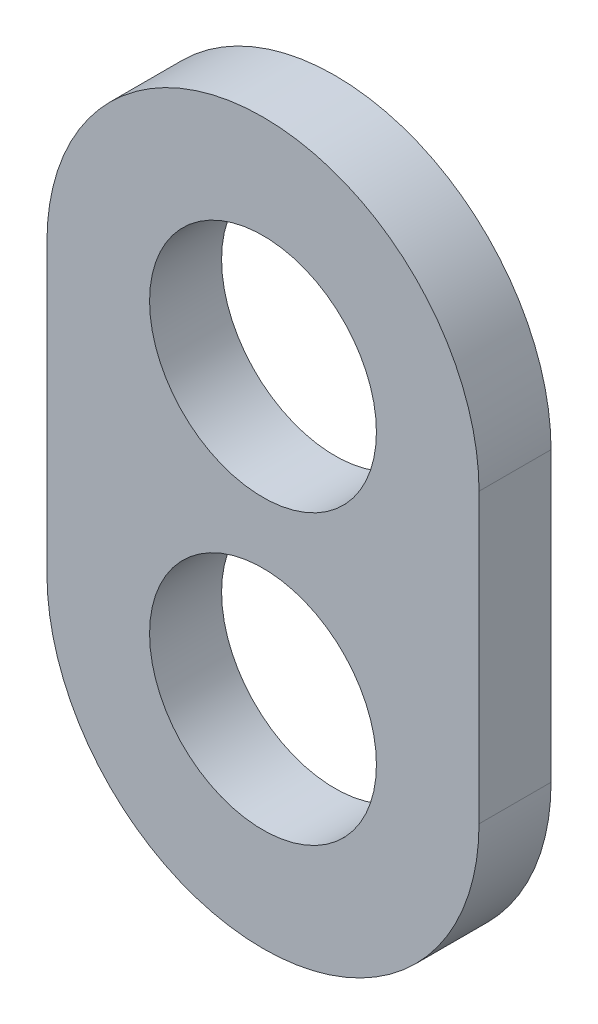
SolidWorks part; units mm, degrees
ref_plane "Front Plane" through (0, 0, 0) normal (0, 0, 1) x (1, 0, 0)
ref_plane "Top Plane" through (0, 0, 0) normal (0, 1, 0) x (1, 0, 0)
ref_plane "Right Plane" through (0, 0, 0) normal (1, 0, 0) x (0, 0, -1)
sketch "Sketch1" plane through (0, 0, 0) normal (0, 0, 1) x (1, 0, 0)
  line L0 (0, 4) -> (0, -4) construction
  line L1 (6, 4) -> (6, -4)
  line L2 (-6, 4) -> (-6, -4)
  line L3 (55, 0) -> (-55, 0) construction
  arc A0 (6, 4) -> (-6, 4) centre (0, 4) ccw
  arc A1 (-6, -4) -> (6, -4) centre (0, -4) ccw
  circle A2 centre (0, 4) radius 3.15
  circle A3 centre (0, -4) radius 3.15
  point P3 (0, 0)
  dimension "D1" = 6
  dimension "D3" = 6.3
  dimension "D2" = 8
extrude "Boss-Extrude1" add sketch "Sketch1" along normal blind 2
